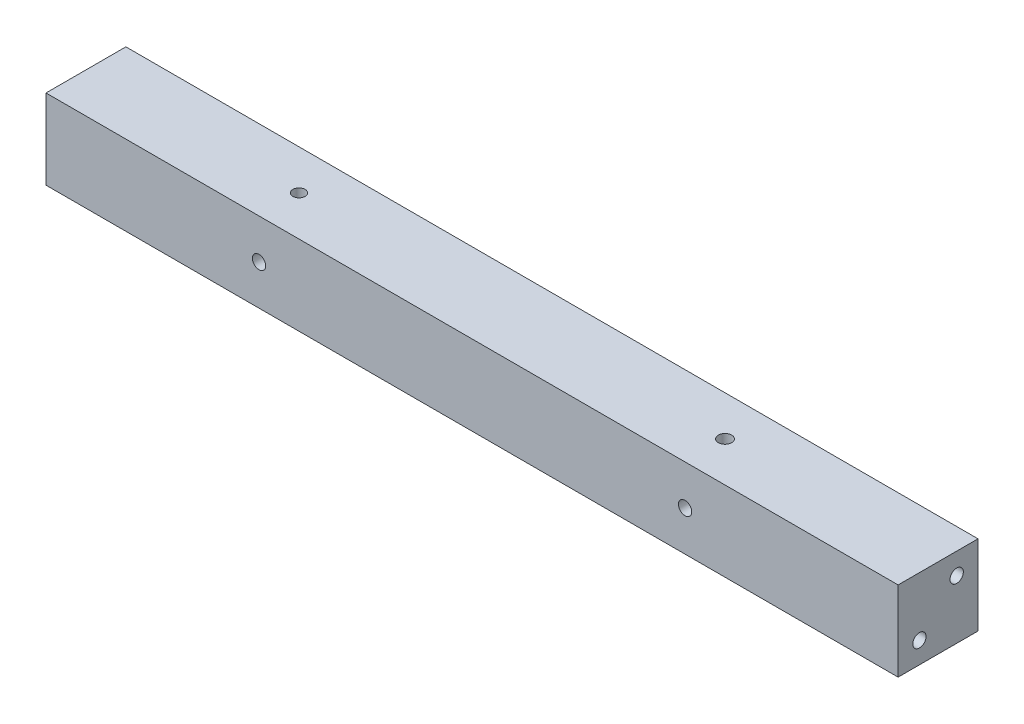
SolidWorks part; units mm, degrees
ref_plane "Ön Düzlem" through (0, 0, 0) normal (0, 0, 1) x (1, 0, 0)
ref_plane "Üst Düzlem" through (0, 0, 0) normal (0, 1, 0) x (1, 0, 0)
ref_plane "Sağ Düzlem" through (0, 0, 0) normal (1, 0, 0) x (0, 0, -1)
sketch "Sketch1" plane through (0, 0, 0) normal (0, 0, 1) x (1, 0, 0)
  line L1 (0, 0) -> (160, 0)
  line L2 (0, 0) -> (0, 15)
  line L3 (0, 15) -> (160, 15)
  line L4 (160, 0) -> (160, 15)
extrude "Boss-Extrude1" add sketch "Sketch1" along normal blind 15
sketch "Sketch2" plane through (0, 0, 15) normal (0, 0, 1) x (1, 0, 0)
  line L0 (0, 15) -> (0, 0) construction
  line L1 (160, 15) -> (0, 15) construction
  line L2 (160, 0) -> (160, 15) construction
  circle A0 centre (40, 7.5) radius 1.25
  circle A1 centre (120, 7.5) radius 1.25
  dimension "D1" = 40
  dimension "D2" = 7.5
  dimension "D3" = 40
  dimension "D4" = 7.5
extrude "Cut-Extrude1" cut sketch "Sketch2" against normal through all
cosmetic thread "Cosmetic Thread1" parameters "D2"=3
cosmetic thread "Cosmetic Thread2" parameters "D2"=3
sketch "Sketch3" plane through (0, 15, 0) normal (0, 1, 0) x (1, 0, 0)
  line L0 (0, -15) -> (0, 0) construction
  line L1 (160, 0) -> (0, 0) construction
  line L2 (160, -15) -> (160, 0) construction
  circle A0 centre (40, -7.5) radius 1.145
  circle A1 centre (120, -7.5) radius 1.25
  dimension "D1" = 40
  dimension "D2" = 7.5
  dimension "D3" = 40
  dimension "D4" = 7.5
extrude "Cut-Extrude2" cut sketch "Sketch3" against normal through all
cosmetic thread "Cosmetic Thread3" parameters "D2"=3
cosmetic thread "Cosmetic Thread4" parameters "D2"=3
sketch "Sketch6" plane through (0, 0, 0) normal (-1, 0, 0) x (0, 0, 1)
  line L0 (0, 15) -> (15, 0) construction
  line L1 (0, 15) -> (0, 0) construction
  line L4 (15, 15) -> (15, 0) construction
  circle A0 centre (4, 11) radius 1.25
  circle A1 centre (11, 4) radius 1.25
  dimension "D1" = 4
  dimension "D2" = 4
extrude "Cut-Extrude5" cut sketch "Sketch6" against normal blind 10
cosmetic thread "Cosmetic Thread9" parameters "D2"=3
cosmetic thread "Cosmetic Thread10" parameters "D2"=3
sketch "Sketch7" plane through (160, 0, 0) normal (1, 0, 0) x (0, 0, -1)
  line L0 (0, 15) -> (-15, 0) construction
  line L1 (0, 0) -> (0, 15) construction
  line L2 (-15, 0) -> (-15, 15) construction
  circle A0 centre (-4, 11) radius 1.25
  circle A1 centre (-11, 4) radius 1.25
  dimension "D1" = 4
  dimension "D2" = 4
extrude "Cut-Extrude6" cut sketch "Sketch7" against normal blind 10
